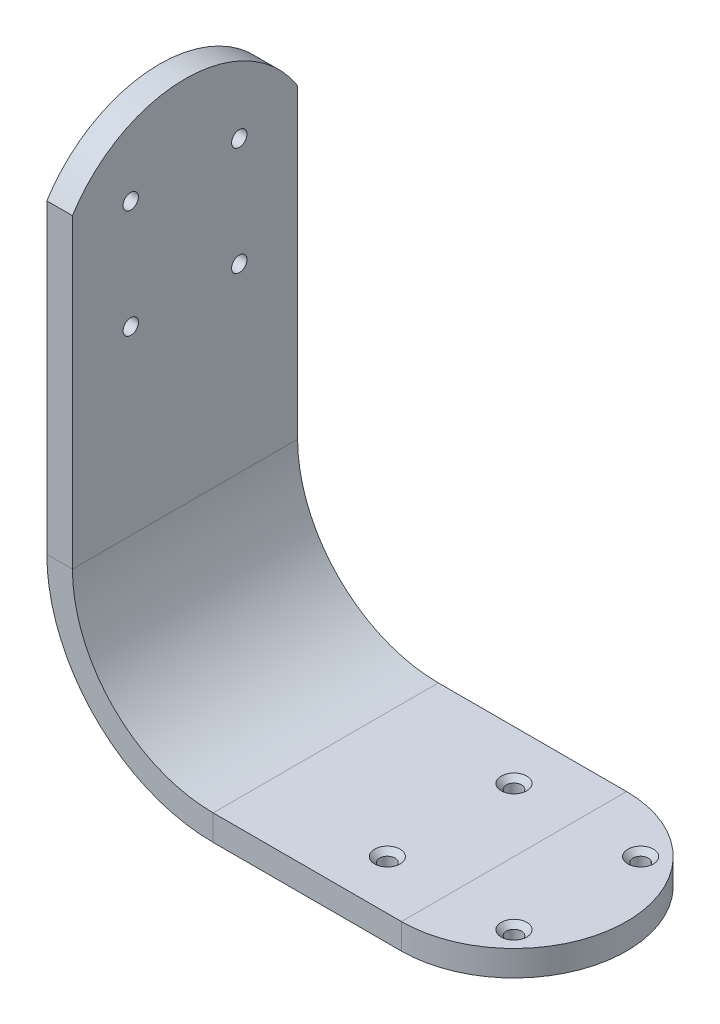
SolidWorks part; units mm, degrees
ref_plane "Спереди" through (0, 0, 0) normal (0, 0, 1) x (1, 0, 0)
ref_plane "Сверху" through (0, 0, 0) normal (0, 1, 0) x (1, 0, 0)
ref_plane "Справа" through (0, 0, 0) normal (1, 0, 0) x (0, 0, -1)
sketch "Эскиз1" plane through (0, 0, 0) normal (0, 0, 1) x (1, 0, 0)
  line L0 (0, 43.9403) -> (0, -28.5217)
  line L1 (30, -58.5217) -> (66.7923, -58.5217)
  line L2 (2.5, 43.4403) -> (2.5, -8.5597) construction
  line L3 (0, 43.9403) -> (3, 43.9403) construction
  line L5 (66.7923, -61.0217) -> (66.7923, -58.5217) construction
  line L6 (66.7923, -58.5217) -> (88.7923, -58.5217)
  arc A0 (0, -28.5217) -> (30, -58.5217) centre (30, -28.5217) ccw
  dimension "D2" = 30
  dimension "D1" = 22
  dimension "D3" = 2.5
  dimension "D4" = 2.5
sketch "Эскиз2" plane through (0, 0, 0) normal (0, 1, 0) x (1, 0, 0)
  line L1 (-2.5, -22) -> (2.5, -22)
  line L2 (-2.5, -22) -> (-2.5, 22)
  line L3 (-2.5, 22) -> (2.5, 22)
  line L4 (2.5, -22) -> (2.5, 22)
  line L5 (-2.5, -22) -> (2.5, 22) construction
  line L6 (-2.5, 22) -> (2.5, -22) construction
  point P0 (0, 0)
  dimension "D1" = 5
  dimension "D2" = 44
sweep "По траектории1" add profiles "Эскиз2" path "Эскиз1"
sketch "Эскиз3" plane through (0, -56.0217, 0) normal (0, 1, 0) x (1, 0, 0)
  line L4 (66.7923, 22) -> (88.7923, 22)
  line L5 (88.7923, 22) -> (88.7923, -22)
  line L6 (88.7923, -22) -> (66.7923, -22)
  arc A0 (66.7923, -22) -> (66.7923, 22) centre (66.7923, 0) ccw
  circle A1 centre (66.7923, 0) radius 43.3473 construction
  line M3 (88.7923, 22) -> (66.7923, 22)
  line M5 (66.7923, -22) -> (88.7923, -22)
  line M6 (88.7923, -22) -> (88.7923, 22)
  dimension "D1" = 44
extrude "Вырез-Вытянуть1" cut sketch "Эскиз3" against normal through all contours A0 L5 M3 | A0 M5 M6
sketch "Эскиз4" plane through (-2.5, 0, 0) normal (-1, 0, 0) x (0, 0, 1)
  line L0 (22, -28.5217) -> (22, 43.9403) construction
  line L1 (-22, -28.5217) -> (-22, 43.9403) construction
  line L2 (-22, 43.9403) -> (22, 43.9403) construction
  line L3 (22, -28.5217) -> (22, 3.5839)
  line L4 (-22, -28.5217) -> (-22, 3.5839)
  line L5 (-22, 43.9403) -> (22, 43.9403)
  line L6 (-22, 31.2967) -> (-22, 43.9403)
  line L7 (22, 31.2967) -> (22, 43.9403)
  circle A1 centre (0, 17.4403) radius 26 construction
  arc A2 (-22, 3.5839) -> (22, 3.5839) centre (0, 17.4403) ccw
  arc A3 (22, 31.2967) -> (-22, 31.2967) centre (0, 17.4403) ccw
  line M2 (22, -28.5217) -> (22, 43.9403)
  line M3 (22, 43.9403) -> (-22, 43.9403)
  line M4 (-22, 43.9403) -> (-22, -28.5217)
extrude "Вырез-Вытянуть2" cut sketch "Эскиз4" against normal through all contours A3 M2 M3 M4
sketch "Эскиз5" plane through (0, -56.0217, 0) normal (0, 1, 0) x (1, 0, 0)
  circle A3 centre (79.1667, 12.3744) radius 1.5 construction
  circle A4 centre (79.1667, -12.3744) radius 1.5 construction
  circle A5 centre (54.4179, -12.3744) radius 1.5 construction
  circle A6 centre (54.4179, 12.3744) radius 1.5 construction
  circle A7 centre (79.1667, 12.3744) radius 1.5
  circle A8 centre (79.1667, -12.3744) radius 1.5
  circle A9 centre (54.4179, -12.3744) radius 1.5
  circle A10 centre (54.4179, 12.3744) radius 1.5
hole_wizard "Зенковка для  винта с потайной головкой с внутренним шестигранником M31" positions "Эскиз6" profile "Эскиз7" countersink size "M3" standard "Ansi Metric" end condition through all
sketch "Эскиз6" plane through (0, -56.0217, 0) normal (0, 1, 0) x (1, 0, 0)
  point P0 (54.4179, -12.3744)
  point P3 (79.1667, -12.3744)
  point P6 (79.1667, 12.3744)
  point P9 (54.4179, 12.3744)
sketch "Эскиз7" plane through (54.4179, -56.0217, 12.3744) normal (1, 0, 0) x (0, 0, 1)
  line L0 (0, 0) -> (0, 5)
  line L1 (0, 5) -> (1.5, 5)
  line L2 (1.5, 5) -> (1.5, 1)
  line L3 (1.5, 1) -> (2.5, 0)
  line L5 (2.5, 0) -> (0, 0)
  line L6 (-1.5, 1) -> (-2.5, 0) construction
  line L11 (0, -6.35) -> (0, 107.95) construction
  dimension "Диаметр сквозного отверстия" = 3
  dimension "Глубина сквозного отверстия" = 5
  dimension "Диаметр передней зенковки" = 5
  dimension "Угол передней зенковки" = 90
sketch "Эскиз8" plane through (-2.5, 0, 0) normal (-1, 0, 0) x (0, 0, 1)
  circle A0 centre (10.6066, 6.8337) radius 1.5 construction
  circle A1 centre (-10.6066, 6.8337) radius 1.5 construction
  circle A2 centre (-10.6066, 28.0469) radius 1.5 construction
  circle A3 centre (10.6066, 28.0469) radius 1.5 construction
  circle A4 centre (10.6066, 6.8337) radius 1.5
  circle A5 centre (-10.6066, 6.8337) radius 1.5
  circle A6 centre (-10.6066, 28.0469) radius 1.5
  circle A7 centre (10.6066, 28.0469) radius 1.5
hole_wizard "Цековка для винта с внутренним шестигранником M31" positions "Эскиз9" profile "Эскиз10" counterbore size "M3" standard "Ansi Metric" end condition through all
sketch "Эскиз9" plane through (-2.5, 0, 0) normal (-1, 0, 0) x (0, 0, 1)
  point P0 (-10.6066, 28.0469)
  point P3 (10.6066, 28.0469)
  point P6 (-10.6066, 6.8337)
  point P9 (10.6066, 6.8337)
sketch "Эскиз10" plane through (-2.5, 28.0469, -10.6066) normal (0, 1, 0) x (0, 0, 1)
  line L0 (0, 0) -> (0, 91.2923)
  line L1 (0, 91.2923) -> (1.5, 91.2923)
  line L3 (1.5, 91.2923) -> (1.5, 1.5)
  line L4 (2.75, 1.5) -> (1.5, 1.5)
  line L5 (2.75, 1.5) -> (2.75, 0.525)
  line L6 (2.75, 0.525) -> (3.275, 0)
  line L7 (3.275, 0) -> (0, 0)
  line L8 (-2.75, 0.525) -> (-3.275, 0) construction
  line L11 (0, -6.35) -> (0, 107.95) construction
  dimension "Диаметр сквозного отверстия" = 3
  dimension "Глубина сквозного отверстия" = 91.2923
  dimension "Диаметр цековки" = 5.5
  dimension "Глубина цековки" = 1.5
  dimension "Диаметр передней зенковки" = 6.55
  dimension "Угол передней зенковки" = 90
